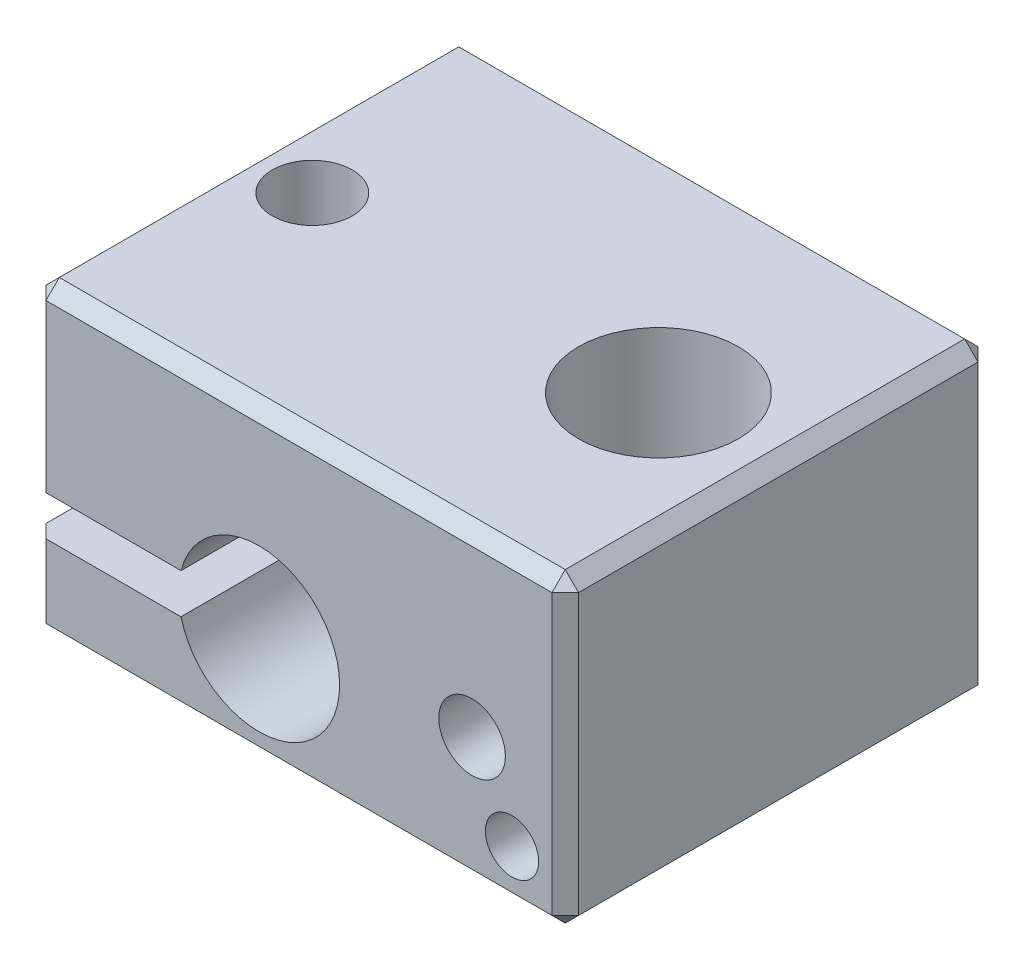
SolidWorks part; units mm, degrees
material "3.0205 (EN-AW 1200)"
ref_plane "Ebene vorne" through (0, 0, 0) normal (0, 0, 1) x (1, 0, 0)
ref_plane "Ebene oben" through (0, 0, 0) normal (0, 1, 0) x (1, 0, 0)
ref_plane "Ebene rechts" through (0, 0, 0) normal (1, 0, 0) x (0, 0, -1)
sketch "Skizze1" plane through (0, 0, 0) normal (0, 0, 1) x (1, 0, 0)
  line L0 (-20, 4.75) -> (-14.4306, 4.75)
  line L1 (0, 0) -> (-20, 0)
  line L2 (0, 0) -> (0, 11.5)
  line L3 (0, 11.5) -> (-20, 11.5)
  line L4 (-20, 0) -> (-20, 3.25)
  line L5 (-14.4306, 3.25) -> (-20, 3.25)
  line L6 (-20, 4.75) -> (-20, 11.5)
  arc A0 (-14.4306, 3.25) -> (-14.4306, 4.75) centre (-11.5, 4) ccw
  dimension "D3" = 3.025
  dimension "D1" = 11.5
  dimension "D2" = 20
  dimension "D4" = 11.5
  dimension "D5" = 4
  dimension "D6" = 1.5
extrude "Aufsatz-Linear austragen1" add sketch "Skizze1" along normal blind 16
sketch "Skizze2" plane through (0, 11.5, 0) normal (0, 1, 0) x (1, 0, 0)
  line L0 (-20, -8) -> (0, -8) construction
  line L1 (-20, -16) -> (-20, 0) construction
  line L2 (0, -16) -> (0, 0) construction
  circle A0 centre (-17.5, -8) radius 1.5
  circle A1 centre (-4.5, -8) radius 3
  dimension "D1" = 3
  dimension "D2" = 6
  dimension "D3" = 4.5
  dimension "D4" = 17.5
extrude "Schnitt-Linear austragen1" cut sketch "Skizze2" against normal up to surface (11.5 mm away) up to face at (-10, 0, 8)
hole_wizard "M3 Gewindebohrung1" positions "Skizze6" profile "Skizze4" tap size "M3" standard "DIN"
sketch "Skizze6" plane through (0, 0, 16) normal (0, 0, 1) x (1, 0, 0)
  line L0 (0, 0) -> (0, 11.5) construction
  point P0 (-3.5, 4.8)
  dimension "D1" = 3.5
  dimension "D2" = 4.8
sketch "Skizze4" plane through (-3.5, 4.8, 16) normal (1, 0, 0) x (0, -1, 0)
  line L0 (0, 0) -> (0, 3.7511)
  line L1 (0, 3.7511) -> (1.25, 3)
  line L2 (1.25, 3) -> (1.25, 0)
  line L5 (1.25, 0) -> (0, 0)
  line L10 (0, 3.7511) -> (-1.25, 3) construction
  line L11 (0, -6.35) -> (0, 107.95) construction
  dimension "Bohrerdurchmesser" = 2.5
  dimension "Bohrungstiefe" = 3
  dimension "Spitzenwinkel" = 118
hole_wizard "Ø1.5 (1.5) Durchmesser Bohrung1" positions "Skizze8" profile "Skizze7" hole size "Ø1.5" standard "DIN"
sketch "Skizze8" plane through (0, 0, 16) normal (0, 0, 1) x (1, 0, 0)
  line L0 (0, 0) -> (0, 11.5) construction
  line L1 (-20, 0) -> (0, 0) construction
  point P0 (-2, 2)
  dimension "D1" = 2
  dimension "D2" = 2
sketch "Skizze7" plane through (-2, 2, 16) normal (1, 0, 0) x (0, -1, 0)
  line L0 (0, 0) -> (0, 4.4506)
  line L1 (0, 4.4506) -> (0.75, 4)
  line L2 (0.75, 4) -> (0.75, 0)
  line L5 (0.75, 0) -> (0, 0)
  line L10 (0, 4.4506) -> (-0.75, 4) construction
  line L11 (0, -6.35) -> (0, 107.95) construction
  dimension "Bohrerdurchmesser" = 1.5
  dimension "Bohrungstiefe" = 4
  dimension "Spitzenwinkel" = 118
hole_wizard "Ø2.0 (2) Durchmesser Bohrung1" positions "Skizze10" profile "Skizze9" hole size "Ø2.0" standard "DIN"
sketch "Skizze10" plane through (0, 0, 16) normal (0, 0, 1) x (1, 0, 0)
  line L0 (-20, 0) -> (0, 0) construction
  line L1 (0, 0) -> (0, 11.5) construction
  point P0 (-2, 2)
  dimension "D1" = 2
  dimension "D2" = 2
sketch "Skizze9" plane through (-2, 2, 16) normal (1, 0, 0) x (0, -1, 0)
  line L0 (0, 0) -> (0, 2.6009)
  line L1 (0, 2.6009) -> (1, 2)
  line L2 (1, 2) -> (1, 0)
  line L5 (1, 0) -> (0, 0)
  line L10 (0, 2.6009) -> (-1, 2) construction
  line L11 (0, -6.35) -> (0, 107.95) construction
  dimension "Bohrerdurchmesser" = 2
  dimension "Bohrungstiefe" = 2
  dimension "Spitzenwinkel" = 118
chamfer "Fase1" distance 0.5 angle 45 14 edges at (-10, 0, 0) (-20, 1.625, 0) (-20, 0, 8) (-20, 8.125, 0) (-20, 8.125, 16) (-20, 1.625, 16) (-10, 0, 16) (0, 0, 8) (0, 5.75, 16) (0, 5.75, 0) (-20, 11.5, 8) (-10, 11.5, 0) (0, 11.5, 8) (-10, 11.5, 16)
